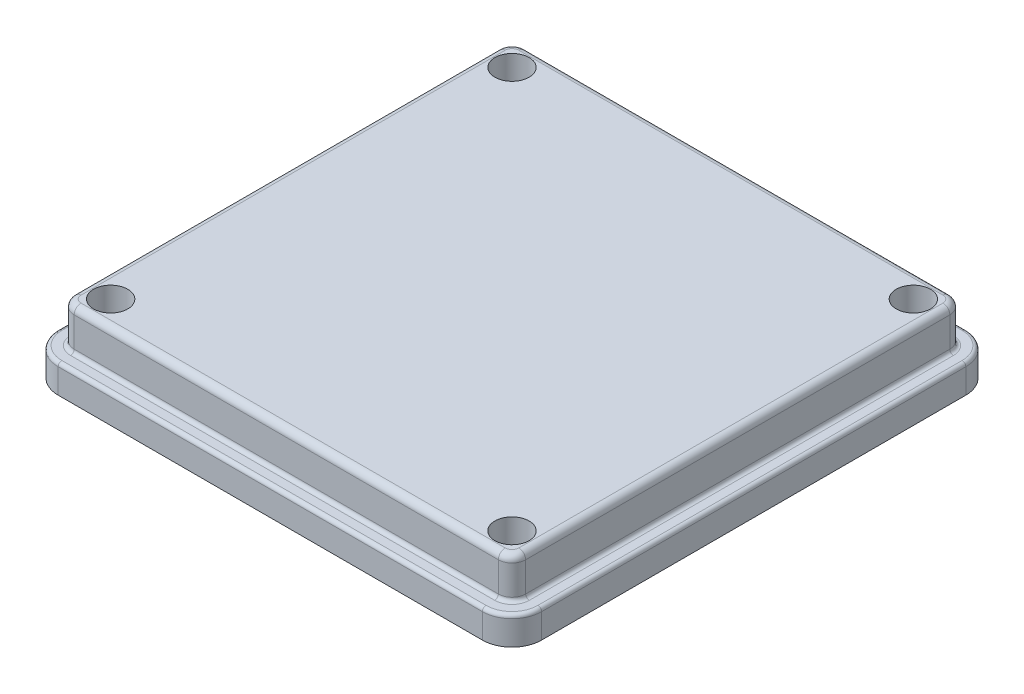
SolidWorks part; units mm, degrees
material "PBT General Purpose"
ref_plane "Front Plane" through (0, 0, 0) normal (0, 0, 1) x (1, 0, 0)
ref_plane "Top Plane" through (0, 0, 0) normal (0, 1, 0) x (1, 0, 0)
ref_plane "Right Plane" through (0, 0, 0) normal (1, 0, 0) x (0, 0, -1)
sketch "Sketch1" plane through (0, 0, 0) normal (0, 1, 0) x (1, 0, 0)
  line L0 (0, 49.5) -> (0, 0) construction
  line L1 (0, 0) -> (49.5, 0) construction
  line L2 (49.5, -46.5) -> (49.5, 46.5)
  line L3 (-46.5, 49.5) -> (46.5, 49.5)
  line L4 (-49.5, -46.5) -> (-49.5, 46.5)
  line L5 (-46.5, -49.5) -> (46.5, -49.5)
  arc A0 (49.5, 46.5) -> (46.5, 49.5) centre (46.5, 46.5) ccw
  arc A1 (-49.5, 46.5) -> (-46.5, 49.5) centre (-46.5, 46.5) cw
  arc A2 (-49.5, -46.5) -> (-46.5, -49.5) centre (-46.5, -46.5) ccw
  arc A3 (49.5, -46.5) -> (46.5, -49.5) centre (46.5, -46.5) cw
  point P17 (-49.5, 0)
  dimension "D1" = 3
  dimension "D2" = 99
  dimension "D3" = 99
extrude "Boss-Extrude1" add sketch "Sketch1" along normal blind 15
fillet "Fillet1" radius 1.5 8 edges at (49.5, 15, 0) (48.6213, 15, 48.6213) (0, 15, 49.5) (-48.6213, 15, 48.6213) (-49.5, 15, 0) (-48.6213, 15, -48.6213) (0, 15, -49.5) (48.6213, 15, -48.6213)
shell "Shell1" thickness 2
sketch "Sketch2" plane through (0, 0, 0) normal (0, 1, 0) x (1, 0, 0)
  line L0 (47.5, -46.5) -> (47.5, 46.5) construction
  line L1 (-46.5, -47.5) -> (46.5, -47.5) construction
  line L2 (-47.5, 46.5) -> (-47.5, -46.5) construction
  line L3 (46.5, 47.5) -> (-46.5, 47.5) construction
  line L4 (47.5, -46.5) -> (47.5, 46.5)
  line L5 (-46.5, -47.5) -> (46.5, -47.5)
  line L6 (-47.5, 46.5) -> (-47.5, -46.5)
  line L7 (46.5, 47.5) -> (-46.5, 47.5)
  line L16 (-53, 46.5) -> (-53, -46.5)
  line L17 (-46.5, -53) -> (46.5, -53)
  line L18 (53, -46.5) -> (53, 46.5)
  line L19 (46.5, 53) -> (-46.5, 53)
  line L20 (-53, 46.5) -> (-53, -46.5)
  line L21 (-46.5, -53) -> (46.5, -53)
  line L22 (53, -46.5) -> (53, 46.5)
  line L23 (46.5, 53) -> (-46.5, 53)
  arc A0 (46.5, -47.5) -> (47.5, -46.5) centre (46.5, -46.5) ccw construction
  arc A1 (-47.5, -46.5) -> (-46.5, -47.5) centre (-46.5, -46.5) ccw construction
  arc A2 (-46.5, 47.5) -> (-47.5, 46.5) centre (-46.5, 46.5) ccw construction
  arc A3 (47.5, 46.5) -> (46.5, 47.5) centre (46.5, 46.5) ccw construction
  arc A4 (46.5, -47.5) -> (47.5, -46.5) centre (46.5, -46.5) ccw
  arc A5 (-47.5, -46.5) -> (-46.5, -47.5) centre (-46.5, -46.5) ccw
  arc A6 (-46.5, 47.5) -> (-47.5, 46.5) centre (-46.5, 46.5) ccw
  arc A7 (47.5, 46.5) -> (46.5, 47.5) centre (46.5, 46.5) ccw
  arc A16 (-46.5, 53) -> (-53, 46.5) centre (-46.5, 46.5) ccw
  arc A17 (-53, -46.5) -> (-46.5, -53) centre (-46.5, -46.5) ccw
  arc A18 (46.5, -53) -> (53, -46.5) centre (46.5, -46.5) ccw
  arc A19 (53, 46.5) -> (46.5, 53) centre (46.5, 46.5) ccw
  arc A20 (-46.5, 53) -> (-53, 46.5) centre (-46.5, 46.5) ccw
  arc A21 (-53, -46.5) -> (-46.5, -53) centre (-46.5, -46.5) ccw
  arc A22 (46.5, -53) -> (53, -46.5) centre (46.5, -46.5) ccw
  arc A23 (53, 46.5) -> (46.5, 53) centre (46.5, 46.5) ccw
  dimension "D1" = 3.5
extrude "Boss-Extrude2" add sketch "Sketch2" along normal blind 6.2
sketch "Sketch3" plane through (0, 0, 0) normal (0, -1, 0) x (1, 0, 0)
  line L12 (-46.5, -51.5) -> (46.5, -51.5)
  line L13 (51.5, -46.5) -> (51.5, 46.5)
  line L14 (46.5, 51.5) -> (-46.5, 51.5)
  line L15 (-51.5, 46.5) -> (-51.5, -46.5)
  line L16 (-46.5, -51.5) -> (46.5, -51.5)
  line L17 (51.5, -46.5) -> (51.5, 46.5)
  line L18 (46.5, 51.5) -> (-46.5, 51.5)
  line L19 (-51.5, 46.5) -> (-51.5, -46.5)
  line L33 (49, -46.5) -> (49, 46.5)
  line L34 (-46.5, -49) -> (46.5, -49)
  line L35 (-49, 46.5) -> (-49, -46.5)
  line L36 (46.5, 49) -> (-46.5, 49)
  line L37 (49, -46.5) -> (49, 46.5)
  line L38 (-46.5, -49) -> (46.5, -49)
  line L39 (-49, 46.5) -> (-49, -46.5)
  line L40 (46.5, 49) -> (-46.5, 49)
  arc A12 (-51.5, -46.5) -> (-46.5, -51.5) centre (-46.5, -46.5) ccw
  arc A13 (46.5, -51.5) -> (51.5, -46.5) centre (46.5, -46.5) ccw
  arc A14 (51.5, 46.5) -> (46.5, 51.5) centre (46.5, 46.5) ccw
  arc A15 (-46.5, 51.5) -> (-51.5, 46.5) centre (-46.5, 46.5) ccw
  arc A16 (-51.5, -46.5) -> (-46.5, -51.5) centre (-46.5, -46.5) ccw
  arc A17 (46.5, -51.5) -> (51.5, -46.5) centre (46.5, -46.5) ccw
  arc A18 (51.5, 46.5) -> (46.5, 51.5) centre (46.5, 46.5) ccw
  arc A19 (-46.5, 51.5) -> (-51.5, 46.5) centre (-46.5, 46.5) ccw
  arc A32 (46.5, -49) -> (49, -46.5) centre (46.5, -46.5) ccw
  arc A33 (-49, -46.5) -> (-46.5, -49) centre (-46.5, -46.5) ccw
  arc A34 (-46.5, 49) -> (-49, 46.5) centre (-46.5, 46.5) ccw
  arc A35 (49, 46.5) -> (46.5, 49) centre (46.5, 46.5) ccw
  arc A36 (46.5, -49) -> (49, -46.5) centre (46.5, -46.5) ccw
  arc A37 (-49, -46.5) -> (-46.5, -49) centre (-46.5, -46.5) ccw
  arc A38 (-46.5, 49) -> (-49, 46.5) centre (-46.5, 46.5) ccw
  arc A39 (49, 46.5) -> (46.5, 49) centre (46.5, 46.5) ccw
  dimension "D1" = 1.5
  dimension "D2" = 1.5
extrude "Cut-Extrude1" cut sketch "Sketch3" against normal blind 5
fillet "Fillet2" radius 0.8 16 edges at (0, 6.2, -49.5) (-48.6213, 6.2, -48.6213) (-49.5, 6.2, 0) (-48.6213, 6.2, 48.6213) (0, 6.2, 49.5) (48.6213, 6.2, 48.6213) (49.5, 6.2, 0) (48.6213, 6.2, -48.6213) (0, 6.2, -53) (51.0962, 6.2, -51.0962) (53, 6.2, 0) (51.0962, 6.2, 51.0962) (0, 6.2, 53) (-51.0962, 6.2, 51.0962) (-53, 6.2, 0) (-51.0962, 6.2, -51.0962)
sketch "Sketch4" plane through (0, 15, 0) normal (0, 1, 0) x (1, 0, 0)
  line L0 (0, 91.6854) -> (0, 0) construction
  line L1 (0, 0) -> (117.8157, 0) construction
  circle A0 centre (44, 44) radius 5
  circle A1 centre (44, -44) radius 5
  circle A2 centre (-44, 44) radius 5
  circle A3 centre (-44, -44) radius 5
  dimension "D1" = 10
  dimension "D2" = 88
  dimension "D3" = 88
extrude "Boss-Extrude4" add sketch "Sketch4" against normal up to surface (14 mm away) from offset 1 up to face at (0, 0, 0) offset against normal yes
hole_wizard "CBORE for M5 Hex Head Bolt1" positions "Sketch6" profile "Sketch5" counterbore size "M5" standard "ISO" end condition through all
sketch "Sketch6" plane through (0, 15, 0) normal (0, 1, 0) x (1, 0, 0)
  point P0 (-44, -44)
  point P3 (44, -44)
  point P6 (-44, 44)
  point P9 (44, 44)
sketch "Sketch5" plane through (-44, 15, 44) normal (1, 0, 0) x (0, 0, 1)
  line L0 (0, 0) -> (0, 15)
  line L1 (0, 15) -> (1.85, 15)
  line L3 (1.85, 15) -> (1.85, 12)
  line L4 (1.85, 12) -> (3.75, 12)
  line L5 (3.75, 12) -> (3.75, 0)
  line L7 (3.75, 0) -> (0, 0)
  line L11 (0, -6.35) -> (0, 107.95) construction
  dimension "Thru Hole Dia." = 3.7
  dimension "Thru Hole Depth" = 15
  dimension "C'Bore Dia." = 7.5
  dimension "C'Bore Depth" = 12
